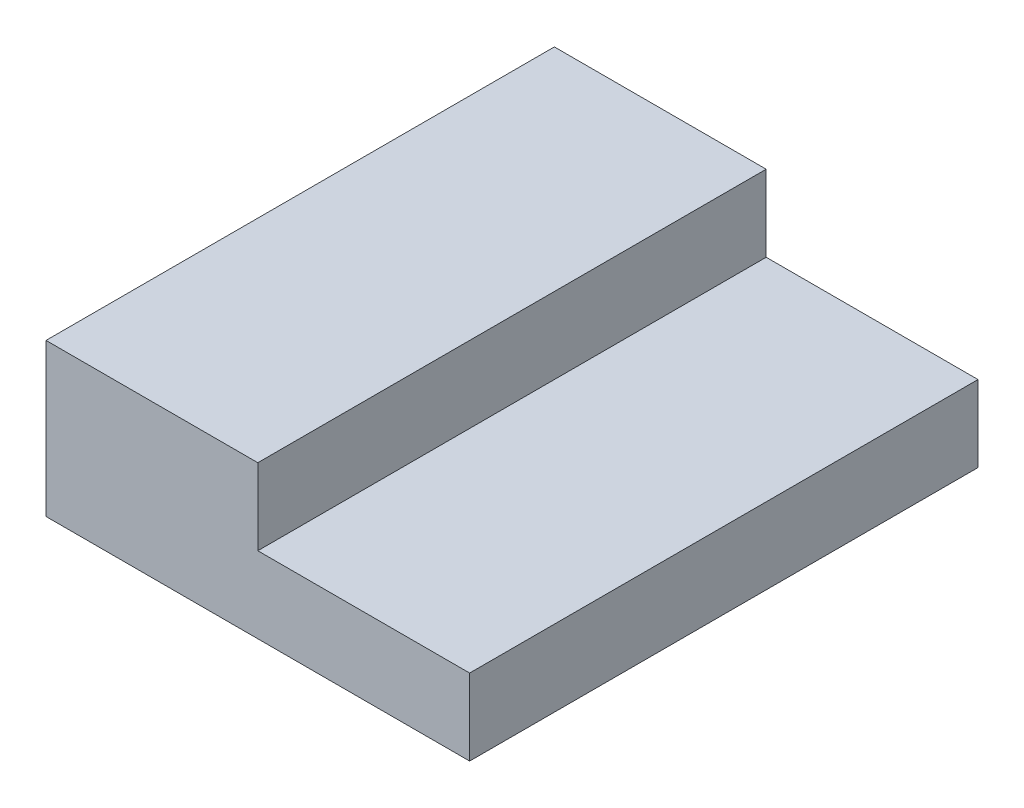
SolidWorks part; units mm, degrees
ref_plane "Plan de face" through (0, 0, 0) normal (0, 0, 1) x (1, 0, 0)
ref_plane "Plan de dessus" through (0, 0, 0) normal (0, 1, 0) x (1, 0, 0)
ref_plane "Plan de droite" through (0, 0, 0) normal (1, 0, 0) x (0, 0, -1)
sketch "Esquisse1" plane through (0, 0, 0) normal (0, 0, 1) x (1, 0, 0)
  line L0 (0, 0) -> (50, 0)
  line L1 (50, 0) -> (50, 9)
  line L2 (50, 9) -> (25, 9)
  line L3 (25, 9) -> (25, 18)
  line L4 (25, 18) -> (0, 18)
  line L5 (0, 18) -> (0, 0)
  dimension "D1" = 50
  dimension "D2" = 18
  dimension "D3" = 9
extrude "Boss.-Extru.1" add sketch "Esquisse1" along normal blind 60
